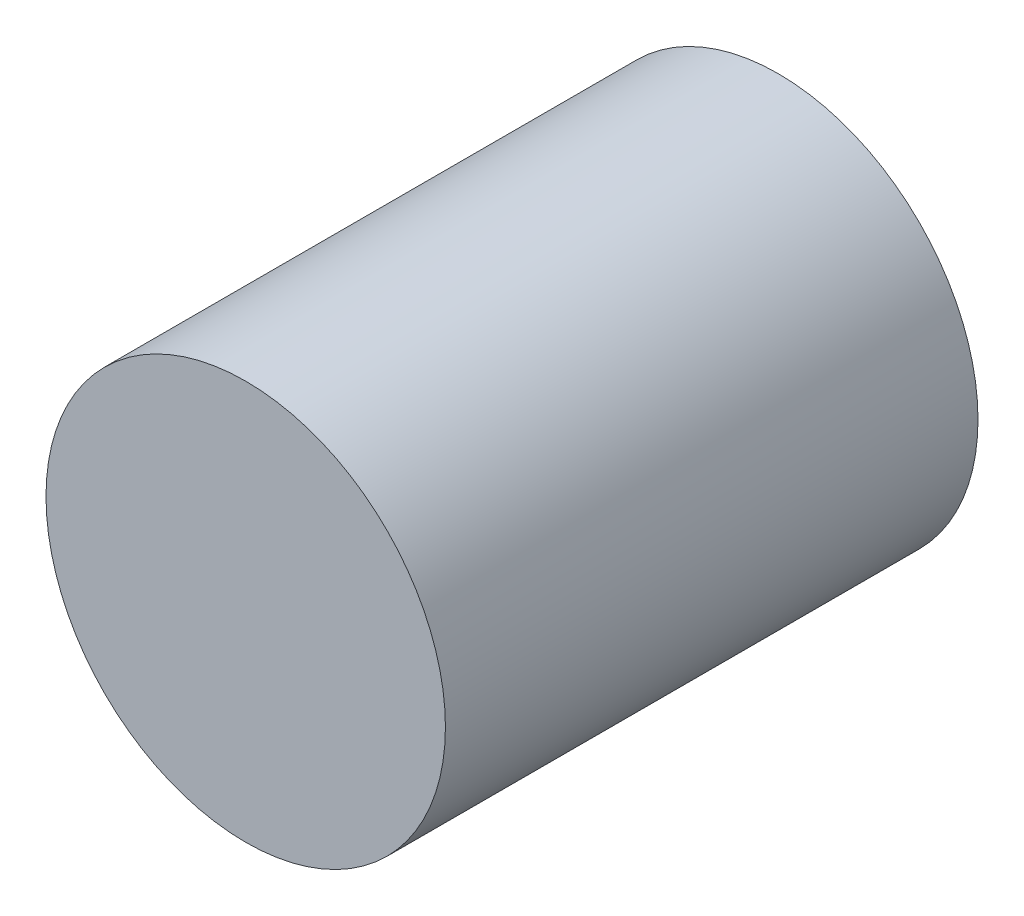
SolidWorks part; units mm, degrees
material "PE haute densité"
ref_plane "Plan de face" through (0, 0, 0) normal (0, 0, 1) x (1, 0, 0)
ref_plane "Plan de dessus" through (0, 0, 0) normal (0, 1, 0) x (1, 0, 0)
ref_plane "Plan de droite" through (0, 0, 0) normal (1, 0, 0) x (0, 0, -1)
sketch "Esquisse1" plane through (0, 0, 0) normal (0, 0, 1) x (1, 0, 0)
  circle A0 centre (0, 0) radius 45
  dimension "D1" = 90
extrude "Boss.-Extru.1" add sketch "Esquisse1" along normal mid plane 120
